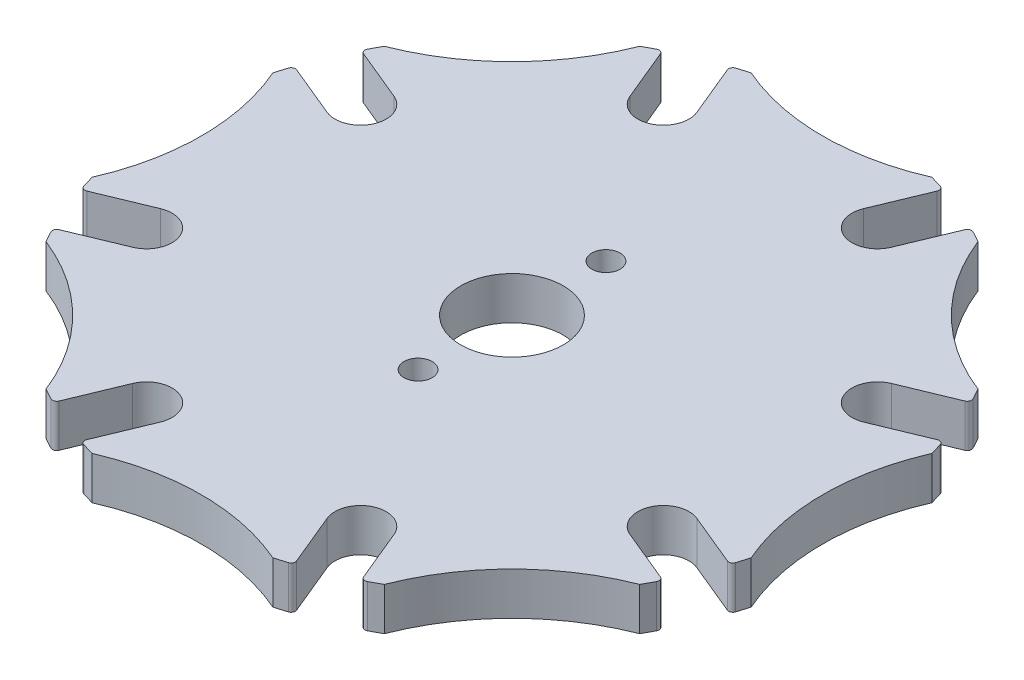
SolidWorks part; units mm, degrees
material "201 Annealed Stainless Steel (SS)"
ref_plane "Front Plane" through (0, 0, 0) normal (0, 0, 1) x (1, 0, 0)
ref_plane "Top Plane" through (0, 0, 0) normal (0, 1, 0) x (1, 0, 0)
ref_plane "Right Plane" through (0, 0, 0) normal (1, 0, 0) x (0, 0, -1)
sketch "Sketch2" plane through (0, 0, 0) normal (0, 1, 0) x (1, 0, 0)
  line L0 (0, 0) -> (62.7561, 0) construction
  line L1 (62.7561, 0) -> (36.9552, 15.3073) construction
  line L2 (36.9552, 15.3073) -> (0, 0) construction
  line L3 (36.9552, 15.3073) -> (30.2627, 12.5352) construction
  line L4 (38.1032, 12.5357) -> (31.4107, 9.7636)
  line L5 (35.8071, 18.079) -> (29.1146, 15.3068)
  line L6 (36.9552, -15.3073) -> (30.2627, -12.5352) construction
  line L7 (35.8071, -18.079) -> (29.1146, -15.3068)
  line L8 (38.1032, -12.5357) -> (31.4107, -9.7636)
  line L9 (15.3073, -36.9552) -> (12.5352, -30.2627) construction
  line L10 (12.5357, -38.1032) -> (9.7636, -31.4107)
  line L11 (18.079, -35.8071) -> (15.3068, -29.1146)
  line L12 (-15.3073, -36.9552) -> (-12.5352, -30.2627) construction
  line L13 (-18.079, -35.8071) -> (-15.3068, -29.1146)
  line L14 (-12.5357, -38.1032) -> (-9.7636, -31.4107)
  line L15 (-36.9552, -15.3073) -> (-30.2627, -12.5352) construction
  line L16 (-38.1032, -12.5357) -> (-31.4107, -9.7636)
  line L17 (-35.8071, -18.079) -> (-29.1146, -15.3068)
  line L18 (-36.9552, 15.3073) -> (-30.2627, 12.5352) construction
  line L19 (-35.8071, 18.079) -> (-29.1146, 15.3068)
  line L20 (-38.1032, 12.5357) -> (-31.4107, 9.7636)
  line L21 (-15.3073, 36.9552) -> (-12.5352, 30.2627) construction
  line L22 (-12.5357, 38.1032) -> (-9.7636, 31.4107)
  line L23 (-18.079, 35.8071) -> (-15.3068, 29.1146)
  line L24 (15.3073, 36.9552) -> (12.5352, 30.2627) construction
  line L25 (18.079, 35.8071) -> (15.3068, 29.1146)
  line L26 (12.5357, 38.1032) -> (9.7636, 31.4107)
  circle A0 centre (36.9552, 15.3073) radius 2.5
  arc A1 (38.1032, 12.5357) -> (35.8071, 18.079) centre (36.9552, 15.3073) ccw
  arc A2 (29.1146, 15.3068) -> (31.4107, 9.7636) centre (30.2627, 12.5352) ccw
  circle A3 centre (62.7561, 0) radius 30
  circle A4 centre (0, 0) radius 40
  circle A5 centre (0, 0) radius 32.7561
  circle A6 centre (62.7561, 0) radius 26.386
  arc A7 (41.2768, 15.239) -> (41.2768, -15.239) centre (62.7561, 0) cw
  arc A8 (41.2768, 15.239) -> (41.2768, -15.239) centre (0, 0) cw
  circle A9 centre (44.3752, -44.3752) radius 26.386
  arc A10 (35.8071, -18.079) -> (38.1032, -12.5357) centre (36.9552, -15.3073) ccw
  arc A11 (31.4107, -9.7636) -> (29.1146, -15.3068) centre (30.2627, -12.5352) ccw
  circle A12 centre (0, -62.7561) radius 26.386
  arc A13 (12.5357, -38.1032) -> (18.079, -35.8071) centre (15.3073, -36.9552) ccw
  arc A14 (15.3068, -29.1146) -> (9.7636, -31.4107) centre (12.5352, -30.2627) ccw
  circle A15 centre (-44.3752, -44.3752) radius 26.386
  arc A16 (-18.079, -35.8071) -> (-12.5357, -38.1032) centre (-15.3073, -36.9552) ccw
  arc A17 (-9.7636, -31.4107) -> (-15.3068, -29.1146) centre (-12.5352, -30.2627) ccw
  circle A18 centre (-62.7561, 0) radius 26.386
  arc A19 (-38.1032, -12.5357) -> (-35.8071, -18.079) centre (-36.9552, -15.3073) ccw
  arc A20 (-29.1146, -15.3068) -> (-31.4107, -9.7636) centre (-30.2627, -12.5352) ccw
  circle A21 centre (-44.3752, 44.3752) radius 26.386
  arc A22 (-35.8071, 18.079) -> (-38.1032, 12.5357) centre (-36.9552, 15.3073) ccw
  arc A23 (-31.4107, 9.7636) -> (-29.1146, 15.3068) centre (-30.2627, 12.5352) ccw
  circle A24 centre (0, 62.7561) radius 26.386
  arc A25 (-12.5357, 38.1032) -> (-18.079, 35.8071) centre (-15.3073, 36.9552) ccw
  arc A26 (-15.3068, 29.1146) -> (-9.7636, 31.4107) centre (-12.5352, 30.2627) ccw
  circle A27 centre (44.3752, 44.3752) radius 26.386
  arc A28 (18.079, 35.8071) -> (12.5357, 38.1032) centre (15.3073, 36.9552) ccw
  arc A29 (9.7636, 31.4107) -> (15.3068, 29.1146) centre (12.5352, 30.2627) ccw
  point P3 (33.6089, 13.9213)
  point P15 (38.5787, 10.5679)
  point P22 (33.6089, -13.9213)
  point P31 (13.9213, -33.6089)
  point P40 (-13.9213, -33.6089)
  point P49 (-33.6089, -13.9213)
  point P58 (-33.6089, 13.9213)
  point P67 (-13.9213, 33.6089)
  point P76 (13.9213, 33.6089)
  point P84 (0, 0)
  dimension "D4" = 5
  dimension "D5" = 3
  dimension "D1" = 22.5
  dimension "D2" = 40
  dimension "D3" = 30
  dimension "D6" = 2
  dimension "D7" = 0.05
  dimension "D8" = 4
  dimension "D9" = 8
extrude "Boss-Extrude1" add sketch "Sketch2" along normal blind 5 contours A29 A5 A26 A23 A20 A17 A14 A11 A2 | A29 L26 A4 A24 L22 A26 A5 | A26 L23 A4 A21 L19 A23 A5 | A23 L20 A4 A18 L16 A20 A5 | A20 L17 A4 A15 L13 A17 A5 | A17 L14 A4 A12 L10 A14 A5 | A14 L11 A4 A9 L7 A11 A5 | A11 L8 A3 A5 | A6 A4 L4 A3 L8 | A5 A3 L4 A2 | A29 A5 A2 L5 A4 A27 L25
fillet "Fillet1" [suppressed] radius 1
sketch "Sketch3" plane through (0, 5, 0) normal (0, 1, 0) x (1, 0, 0)
  circle A0 centre (0, 0) radius 11
  circle A1 centre (0, 11) radius 1.65
  circle A2 centre (0, 0) radius 11
  circle A4 centre (0, 0) radius 10
  circle A6 centre (0, 0) radius 6
  circle A7 centre (0, -11) radius 1.65
  arc A10 (-10.5679, 38.5787) -> (10.5679, 38.5787) centre (0, 62.7561) ccw construction
  point P7 (0, 0)
  point P17 (0, 0)
  point P18 (0, 36.37)
  dimension "D1" = 22
  dimension "D2" = 3.3
  dimension "D4" = 12
  dimension "D3" = 2
extrude "Cut-Extrude1" cut sketch "Sketch3" against normal blind 10 contours A0 A1 | A0 A1 | A4 A7 | A4 A7 | A6
fillet "Fillet2" radius 0.5 16 edges at (-12.4926, 2.5, 37.9991) (12.4926, 2.5, 37.9991) (18.0359, 2.5, 35.703) (35.703, 2.5, 18.0359) (37.9991, 2.5, 12.4926) (37.9991, 2.5, -12.4926) (35.703, 2.5, -18.0359) (18.0359, 2.5, -35.703) (12.4926, 2.5, -37.9991) (-12.4926, 2.5, -37.9991) (-18.0359, 2.5, -35.703) (-35.703, 2.5, -18.0359) (-37.9991, 2.5, -12.4926) (-37.9991, 2.5, 12.4926) (-35.703, 2.5, 18.0359) (-18.0359, 2.5, 35.703)
equation "\"angle\"= 22.5"
equation "\"driveR\"= 40"
equation "\"D1@Sketch2\"=\"angle\""
equation "\"D2@Sketch2\"=\"driveR\""
equation "\"wheelR\"= 30"
equation "\"D3@Sketch2\"=\"wheelR\""
equation "\"pin\"= 5"
equation "\"D4@Sketch2\"=\"pin\""
equation "\"D5@Sketch2\"=(\"pin\"/2)+\"tol\"*10"
equation "\"tol\"= 0.05"
equation "\"D7@Sketch2\"=\"tol\""
